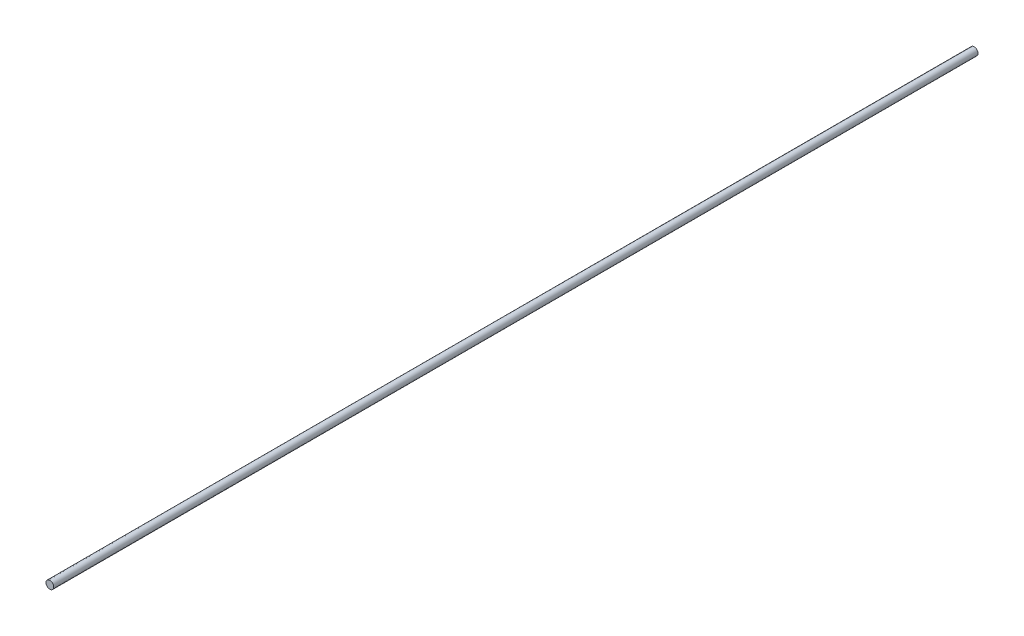
SolidWorks part; units mm, degrees
material "Plain Carbon Steel"
ref_plane "Front Plane" through (0, 0, 0) normal (0, 0, 1) x (1, 0, 0)
ref_plane "Top Plane" through (0, 0, 0) normal (0, 1, 0) x (1, 0, 0)
ref_plane "Right Plane" through (0, 0, 0) normal (1, 0, 0) x (0, 0, -1)
sketch "Sketch1" plane through (0, 0, 0) normal (0, 0, 1) x (1, 0, 0)
  circle A0 centre (0, 0) radius 4
  dimension "D1" = 8
extrude "Boss-Extrude1" add sketch "Sketch1" along normal blind 960
